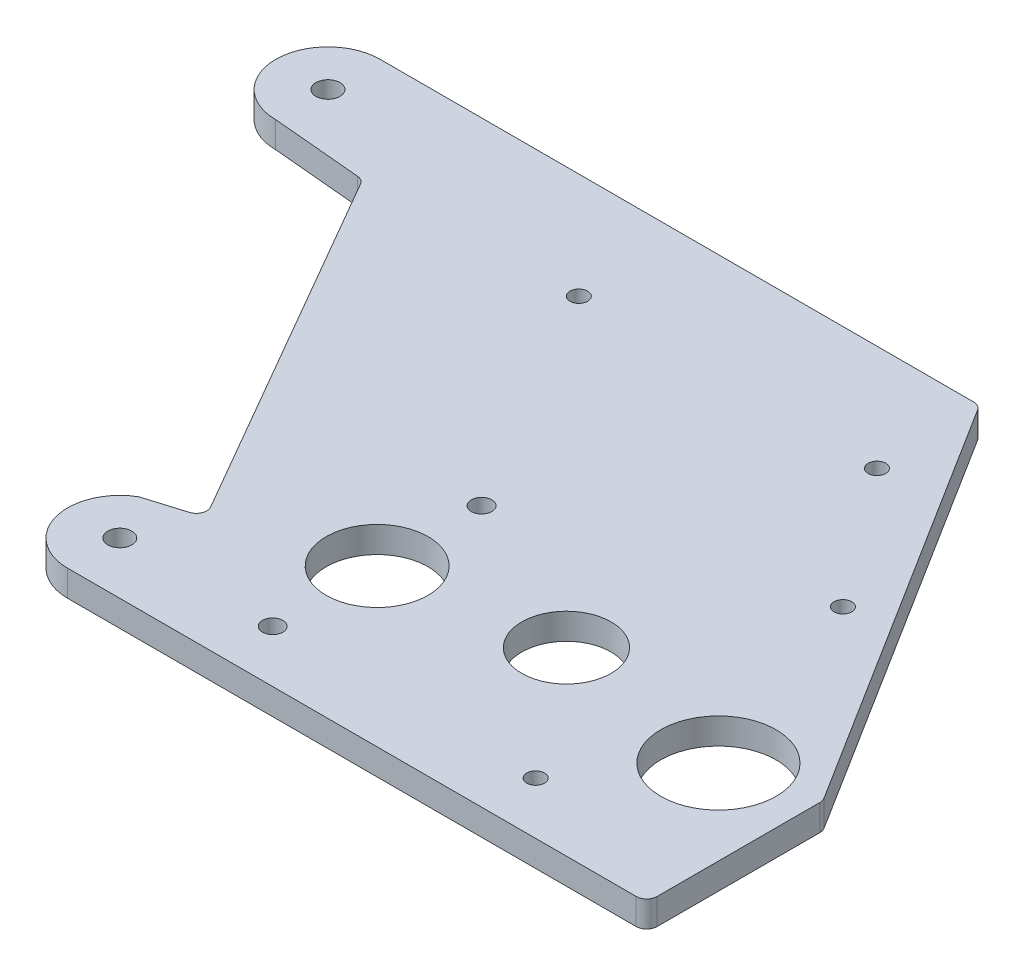
SolidWorks part; units mm, degrees
ref_plane "Front Plane" through (0, 0, 0) normal (0, 0, 1) x (1, 0, 0)
ref_plane "Top Plane" through (0, 0, 0) normal (0, 1, 0) x (1, 0, 0)
ref_plane "Right Plane" through (0, 0, 0) normal (1, 0, 0) x (0, 0, -1)
sketch "Sketch1" plane through (0, 0, 0) normal (0, 1, 0) x (1, 0, 0)
  line L0 (-190.7858, 72.591) -> (-106.965, -72.591)
  line L1 (-190.7858, 72.591) -> (190.7858, 72.591)
  line L2 (-190.7858, 72.591) -> (-190.7858, -72.591)
  line L3 (-190.7858, -72.591) -> (190.7858, -72.591)
  line L4 (190.7858, 72.591) -> (190.7858, -72.591)
  line L5 (-190.7858, 72.591) -> (190.7858, -72.591) construction
  line L6 (-190.7858, -72.591) -> (190.7858, 72.591) construction
  line L7 (-161.4564, 72.591) -> (-77.6356, -72.591)
  line L8 (-176.1211, 72.591) -> (-92.3003, -72.591) construction
  line L9 (-62.4429, -34.491) -> (-22.2218, -28.6714) construction
  line L10 (-22.2218, -28.6714) -> (20.5643, -34.491) construction
  line L11 (20.5643, -34.491) -> (-62.4429, -34.491) construction
  line L12 (47.5645, 72.591) -> (47.5645, -72.591)
  line L13 (-168.7887, 47.191) -> (-145.5814, 45.0947)
  line L14 (-105.9826, -48.8924) -> (-93.5106, -45.0947)
  circle A0 centre (-62.4429, -34.491) radius 32.2072
  circle A1 centre (-62.4429, -34.491) radius 12.3825
  circle A2 centre (-62.4429, -9.091) radius 2.4892
  circle A3 centre (-62.4429, -59.891) radius 2.4892
  circle A4 centre (-22.2218, -28.6714) radius 10.8585
  circle A5 centre (20.5643, -34.491) radius 14.0335
  circle A6 centre (-168.7887, 59.891) radius 2.921
  circle A7 centre (-99.6326, -59.891) radius 2.921
  circle A8 centre (-168.7887, 59.891) radius 12.7
  circle A9 centre (-99.6326, -59.891) radius 12.7
  point P0 (0, 0)
  dimension "D2" = 120
  dimension "D5" = 64.4144
  dimension "D6" = 24.765
  dimension "D7" = 4.9784
  dimension "D8" = 4.9784
  dimension "D9" = 50.8
  dimension "D10" = 25.4
  dimension "D11" = 12.7
  dimension "D15" = 21.717
  dimension "D16" = 28.067
  dimension "D18" = 5.842
  dimension "D19" = 5.842
  dimension "D20" = 12.7
  dimension "D21" = 12.7
  dimension "D22" = 25.4
  dimension "D23" = 31.75
  dimension "D1" = 145.1819
  dimension "D3" = 25.4
  dimension "D4" = 12.7
  dimension "D12" = 40.64
  dimension "D13" = 43.18
  dimension "D14" = 83.0072
  dimension "D17" = 27.0002
  dimension "D24" = 31.75
  dimension "D25" = 125.161
  dimension "D26" = 23.3018
extrude "Boss-Extrude1" add sketch "Sketch1" along normal blind 6.35 contours A4 A0 L7 L3 L12 L1 A5 | A4 A0 A3 A2 A1 | A9 L14 A7 | A9 L7 L14 | A9 L3 L7 | A8 A6 | A8 L13 L7 | A8 L7 L1
sketch "Sketch2" plane through (0, 6.35, 0) normal (0, 1, 0) x (1, 0, 0)
  line L0 (-145.5814, 45.0947) -> (-93.5106, -45.0947)
  line L1 (-154.124, 72.591) -> (-70.3032, -72.591)
  line L2 (-168.7887, 72.591) -> (47.5645, 72.591) construction
  line L3 (-99.6326, -72.591) -> (47.5645, -72.591) construction
  line L4 (-150.4579, 66.241) -> (47.5645, 66.241)
  line L5 (47.5645, 72.591) -> (47.5645, -72.591) construction
  line L6 (41.2145, 72.591) -> (41.2145, -72.591)
  line L7 (-73.9694, -66.241) -> (41.2145, -66.241)
  line L8 (-62.4429, -9.091) -> (-105.9359, 66.241) construction
  line L9 (-22.2218, -28.6714) -> (-22.2218, 66.241) construction
  line L10 (20.5643, -34.491) -> (20.5643, -66.241) construction
  line L11 (-22.2218, -28.6714) -> (1.5143, -59.891) construction
  line L12 (-22.2218, -28.6714) -> (20.5643, -34.491) construction
  line L13 (-139.2615, 46.8482) -> (41.2145, 46.8482) construction
  line L14 (-141.0946, 50.0232) -> (41.2145, 50.0232)
  line L15 (-137.4284, 43.6732) -> (41.2145, 43.6732)
  line L16 (-109.602, 66.241) -> (-72.6391, 2.2194)
  line L17 (-102.2697, 66.241) -> (-66.0124, 3.4415)
  line L18 (-25.3968, 66.241) -> (-25.3968, -11.487)
  line L19 (-19.0468, 66.241) -> (-19.0468, -11.487)
  line L20 (-4.7663, -27.8414) -> (0.7737, -28.5949)
  line L21 (-5.6221, -34.1334) -> (-0.0821, -34.887)
  line L22 (34.8645, 72.591) -> (34.8645, -72.591)
  line L23 (-14.3487, -44.2726) -> (-8.4556, -52.0238)
  line L24 (-9.2938, -40.4294) -> (-3.4006, -48.1806)
  line L25 (-19.0468, 66.241) -> (34.8645, -19.5935)
  line L26 (-27.416, 66.241) -> (22.9704, -13.9814)
  line L27 (-13.2415, 43.6732) -> (22.9704, -13.9814) construction
  line L28 (4.8645, 14.8459) -> (-19.0468, -0.1724) construction
  line L29 (-19.0468, 66.241) -> (-23.0351, 72.591)
  line L30 (-27.416, 66.241) -> (-31.4043, 72.591)
  line L31 (34.8645, -19.5935) -> (47.5645, -39.8137)
  line L32 (2.8001, 13.5493) -> (-22.2218, -28.6714) construction
  line L33 (2.8001, 13.5493) -> (20.5643, -34.491) construction
  line L34 (-4.5097, 7.4426) -> (-16.192, -12.2694)
  line L35 (0.953, 4.2051) -> (-10.7292, -15.5069)
  line L36 (2.9367, 4.0253) -> (10.5095, -16.454)
  line L37 (8.8926, 6.2276) -> (16.4653, -14.2517)
  circle A0 centre (-62.4429, -34.491) radius 38.1
  circle A1 centre (-22.2218, -28.6714) radius 17.4752
  circle A2 centre (20.5643, -34.491) radius 20.6502
  circle A3 centre (1.5143, -59.891) radius 2.1527
  circle A4 centre (1.5143, -59.891) radius 12.7
  circle A5 centre (-94.7395, 46.8482) radius 2.1527
  circle A6 centre (-94.7395, 46.8482) radius 9.525
  circle A7 centre (-22.2218, 46.8482) radius 2.1527
  circle A8 centre (-22.2218, 46.8482) radius 9.525
  circle A9 centre (2.8001, 13.5493) radius 9.525
  circle A10 centre (2.8001, 13.5493) radius 2.1527
  point P68 (-13.2415, 43.6732)
  line M27 (-99.6326, -72.591) -> (47.5645, -72.591)
  line M28 (47.5645, -72.591) -> (47.5645, 72.591)
  line M29 (47.5645, 72.591) -> (-168.7887, 72.591)
  dimension "D5" = 34.9504
  dimension "D6" = 41.3004
  dimension "D7" = 4.3053
  dimension "D9" = 25.4
  dimension "D11" = 4.3053
  dimension "D12" = 19.05
  dimension "D13" = 4.3053
  dimension "D14" = 19.05
  dimension "D21" = 19.05
  dimension "D22" = 4.3053
  dimension "D1" = 6.35
  dimension "D2" = 6.35
  dimension "D3" = 6.35
  dimension "D4" = 6.35
  dimension "D8" = 19.05
  dimension "D10" = 1.7536
  dimension "D15" = 6.35
  dimension "D16" = 6.35
  dimension "D17" = 6.35
  dimension "D18" = 6.35
  dimension "D19" = 12.7
  dimension "D20" = 6.35
  dimension "D23" = 6.35
  dimension "D24" = 6.35
extrude "Cut-Extrude2" cut sketch "Sketch2" against normal through all contours L6 L31 L4 M28 | L6 L4 M29 M28 | L4 L22 L14 L6 | L22 L4 L6 M29 | L29 L4 L22 M29 | L4 L25 L14 L22 | L14 L25 L15 L22 | L14 L22 L15 L6 | L15 L25 L22 | A2 L31 L6 L15 L22 | L31 L6 M27 M28 | A5 | A7 | A10 | A3 | L31 A2
fillet "Fillet1" radius 2.54 5 edges at (-93.5106, 3.175, 45.0947) (41.2145, 3.175, 72.591) (-145.5814, 3.175, -45.0947) (-23.0351, 3.175, -72.591) (41.2145, 3.175, 29.7036)
